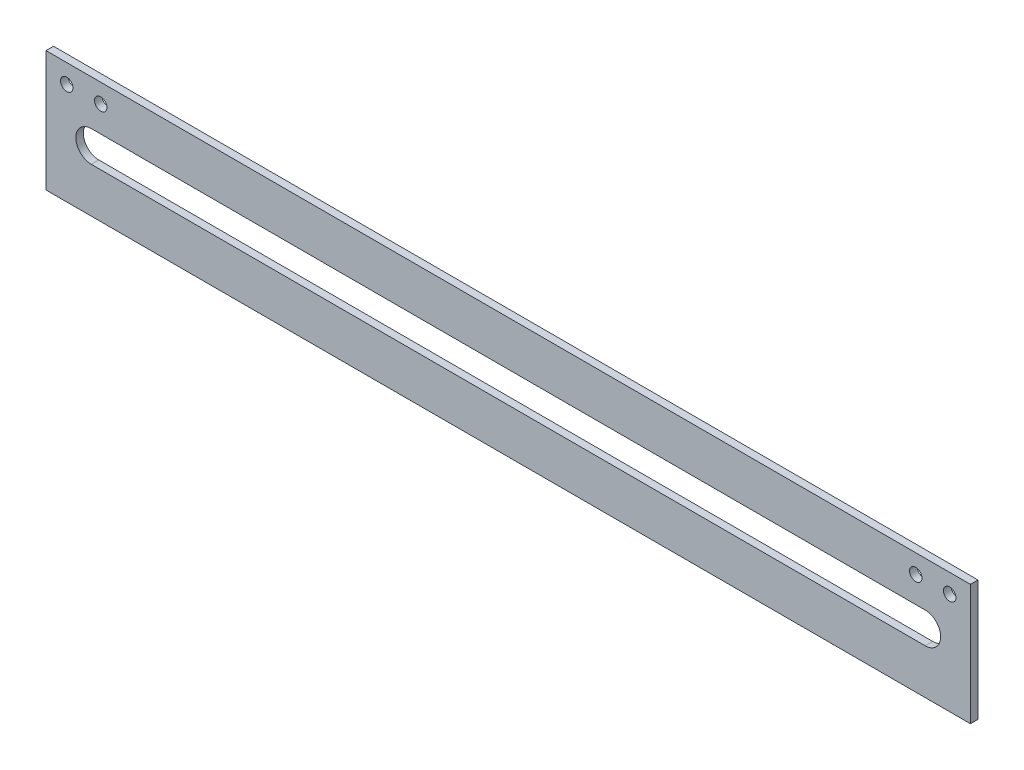
SolidWorks part; units mm, degrees
ref_plane "前视基准面" through (0, 0, 0) normal (0, 0, 1) x (1, 0, 0)
ref_plane "上视基准面" through (0, 0, 0) normal (0, 1, 0) x (1, 0, 0)
ref_plane "右视基准面" through (0, 0, 0) normal (1, 0, 0) x (0, 0, -1)
sketch "草图1" plane through (0, 0, 0) normal (0, 0, 1) x (1, 0, 0)
  line L0 (12, 16) -> (233, 16) construction
  line L1 (0, 0) -> (245, 0)
  line L2 (0, 0) -> (0, 32)
  line L3 (0, 32) -> (245, 32)
  line L4 (245, 0) -> (245, 32)
  line L5 (12, 20.1) -> (233, 20.1)
  line L6 (12, 11.9) -> (233, 11.9)
  line L7 (122.5, 32) -> (122.5, 36.1029)
  line L8 (10, 32) -> (10, 0) construction
  arc A0 (12, 20.1) -> (12, 11.9) centre (12, 16) ccw
  arc A1 (233, 11.9) -> (233, 20.1) centre (233, 16) ccw
  circle A2 centre (14.5, 27) radius 1.65
  circle A3 centre (5.5, 27) radius 1.65
  circle A4 centre (230.5, 27) radius 1.65
  circle A5 centre (239.5, 27) radius 1.65
  point P7 (122.5, 16)
  dimension "D4" = 4.1
  dimension "D6" = 9
  dimension "D7" = 3.3
  dimension "D1" = 245
  dimension "D2" = 16
  dimension "D3" = 32
  dimension "D5" = 12
  dimension "D8" = 5
  dimension "D9" = 10
extrude "凸台-拉伸1" add sketch "草图1" along normal blind 2
